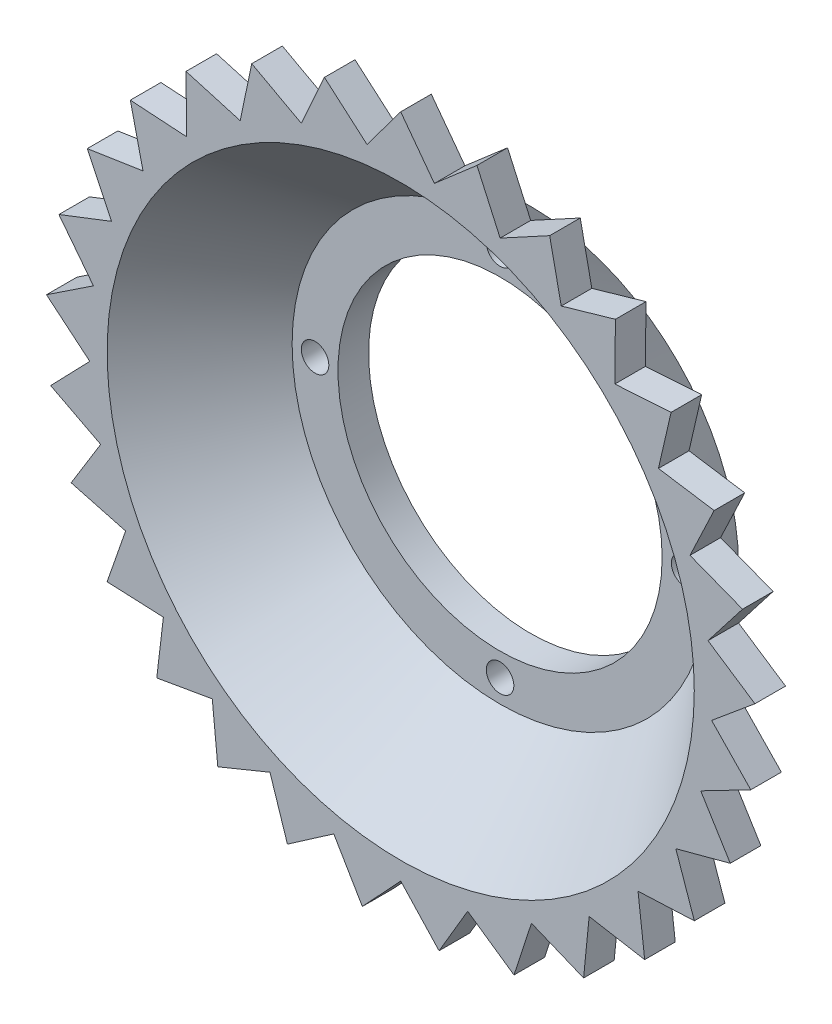
SolidWorks part; units mm, degrees
ref_plane "Plan de face" through (0, 0, 0) normal (0, 0, 1) x (1, 0, 0)
ref_plane "Plan de dessus" through (0, 0, 0) normal (0, 1, 0) x (1, 0, 0)
ref_plane "Plan de droite" through (0, 0, 0) normal (1, 0, 0) x (0, 0, -1)
sketch "Esquisse1" plane through (0, 0, 0) normal (0, 0, 1) x (1, 0, 0)
  line L0 (-11.1734, 101) -> (0, 0)
  line L1 (0, 0) -> (11.1734, 101)
  line L2 (11.1734, 101) -> (0, 116)
  line L3 (0, 116) -> (-11.1734, 101)
  line L4 (0, -55) -> (0, 55) construction
  line L5 (0, 116) -> (0, 0) construction
  dimension "D1" = 116
  dimension "D2" = 12.626
  dimension "D3" = 101
extrude "Boss.-Extru.1" add sketch "Esquisse1" along normal blind 10
pattern_circular "Répétition circulaire1" count 29 over 360 about axis through (0, 0, 0) along (0, 0, 1) of bodies 101
sketch "Esquisse3" plane through (0, 0, 0) normal (0, 0, 1) x (1, 0, 0)
  circle A0 centre (0, 0) radius 100
  dimension "D1" = 200
extrude "Enlèv. mat.-Extru.1" cut sketch "Esquisse3" along normal through all
sketch "Esquisse4" plane through (0, 0, 0) normal (1, 0, 0) x (0, 0, -1)
  line L0 (-61.0736, 0) -> (86.288, 0) construction
  line L1 (22.49, 53) -> (32.49, 53)
  line L2 (32.49, 53) -> (32.49, 68)
  line L3 (32.49, 68) -> (0, 96)
  line L4 (0, 96) -> (0, 101)
  line L5 (0, 101) -> (-10, 101)
  line L6 (-10, 101) -> (-10, 96)
  line L7 (-10, 96) -> (22.49, 68)
  line L8 (22.49, 68) -> (22.49, 53)
  line L9 (-10, 100) -> (-10, 99.3936) construction
  dimension "D1" = 10
  dimension "D2" = 10
  dimension "D4" = 32.49
  dimension "D5" = 53
  dimension "D6" = 68
  dimension "D7" = 101
  dimension "D8" = 180
  dimension "D9" = 5
revolve "Révolution1" add sketch "Esquisse4" angle 360 about L0
sketch "Esquisse5" plane through (0, 0, -22.49) normal (0, 0, 1) x (1, 0, 0)
  line L0 (0, -23.3695) -> (0, 23.3695) construction
  line L1 (23.3695, 0) -> (-23.3695, 0) construction
  circle A0 centre (0, 0) radius 60.5
  point P0 (0, 60.5)
  point P4 (60.5, 0)
  point P8 (0, -60.5)
  point P10 (-60.5, 0)
  dimension "D1" = 121
hole_wizard "Dégagement M81" positions "Esquisse5" profile "Esquisse6" hole size "M8" standard "ISO" end condition through all
sketch "Esquisse6" plane through (0, 60.5, -22.49) normal (1, 0, 0) x (0, -1, 0)
  line L0 (0, 0) -> (0, 10)
  line L1 (0, 10) -> (4.5, 10)
  line L2 (4.5, 10) -> (4.5, 0)
  line L5 (4.5, 0) -> (0, 0)
  line L11 (0, -6.35) -> (0, 107.95) construction
  dimension "Diamètre du perçage jusqu'au prochain" = 9
  dimension "Profondeur du perçage jusqu'au prochain" = 10
